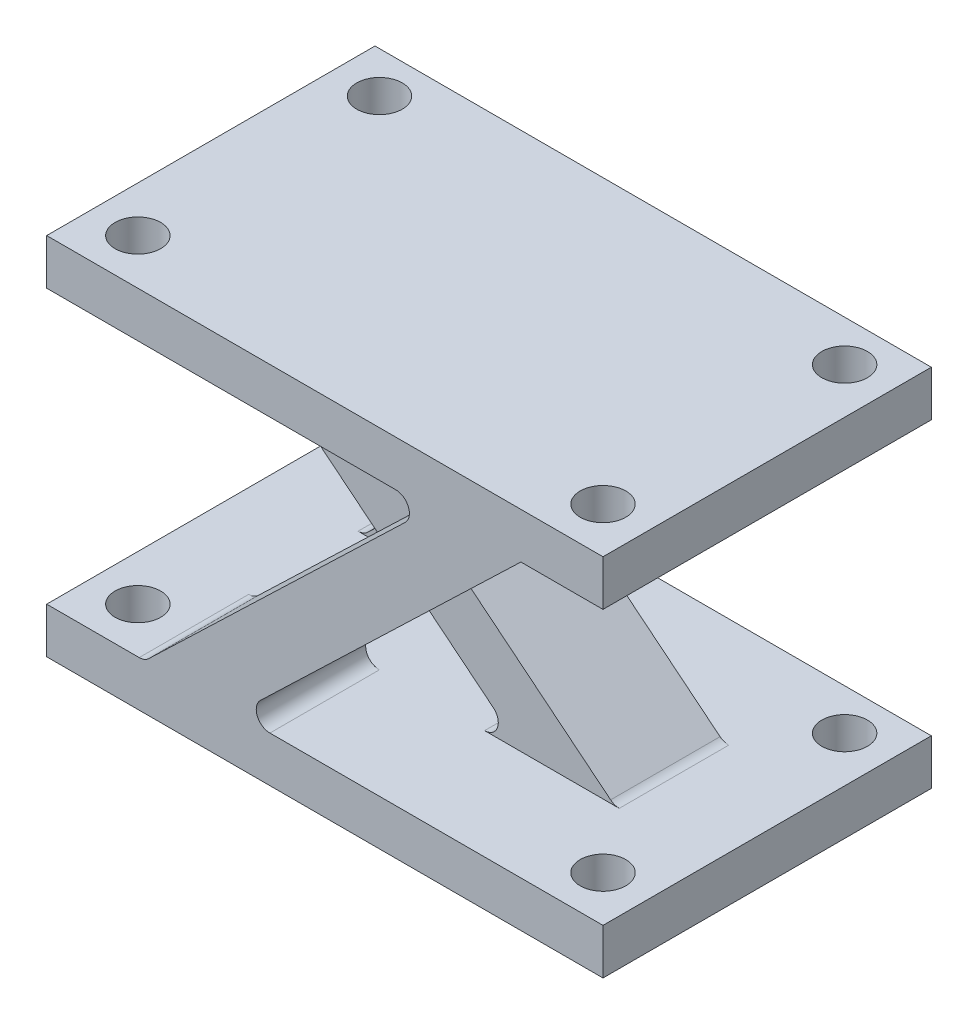
SolidWorks part; units mm, degrees
ref_plane "Front Plane" through (0, 0, 0) normal (0, 0, 1) x (1, 0, 0)
ref_plane "Top Plane" through (0, 0, 0) normal (0, 1, 0) x (1, 0, 0)
ref_plane "Right Plane" through (0, 0, 0) normal (1, 0, 0) x (0, 0, -1)
sketch "Sketch1" plane through (0, 0, 0) normal (0, 1, 0) x (1, 0, 0)
  line L1 (-30.5, -18) -> (30.5, -18)
  line L2 (-30.5, -18) -> (-30.5, 18)
  line L3 (-30.5, 18) -> (30.5, 18)
  line L4 (30.5, -18) -> (30.5, 18)
  line L5 (-30.5, -18) -> (30.5, 18) construction
  line L6 (-30.5, 18) -> (30.5, -18) construction
  circle A0 centre (-25.5, 13.494) radius 2.5
  circle A1 centre (25.5, 13.494) radius 2.5
  circle A2 centre (25.5, -13) radius 2.5
  circle A3 centre (-25.5, -13) radius 2.5
  point P0 (0, 0)
  point P8 (-26.5, -15.2276)
  point P9 (0, 0)
  point P10 (-25.5, -15)
  point P17 (-46.5891, -11.4362)
  dimension "D3" = 5
  dimension "D1" = 36
  dimension "D2" = 61
  dimension "D4" = 5
  dimension "D5" = 4.506
  dimension "D8" = 5
  dimension "D9" = 5
  dimension "D6" = 2
  dimension "D7" = 2
extrude "Boss-Extrude1" add sketch "Sketch1" along normal blind 5
sketch "Sketch4" plane through (0, 0, 18) normal (0, 0, 1) x (1, 0, 0)
  line L0 (19.75, 5) -> (-17.25, 35)
  line L1 (-30.5, 5) -> (30.5, 5) construction
  line L2 (-17.25, 35) -> (-27.25, 35)
  line L3 (-27.25, 35) -> (9.75, 5)
  line L4 (9.75, 5) -> (19.75, 5)
  line L5 (30.5, 5) -> (30.5, 0) construction
  point P8 (0, 0)
  dimension "D1" = 30
  dimension "D2" = 10.75
  dimension "D3" = 20.75
  dimension "D4" = 57.75
extrude "Boss-Extrude3" add sketch "Sketch4" against normal mid plane 12 from surface at -18 starting at plane "Front Plane"
sketch "Sketch3" plane through (0, 0, 18) normal (0, 0, 1) x (1, 0, 0)
  line L0 (-19.75, 5) -> (11.5, 35)
  line L1 (-30.5, 5) -> (30.5, 5) construction
  line L2 (11.5, 35) -> (21.5, 35)
  line L3 (21.5, 35) -> (-9.75, 5)
  line L4 (-9.75, 5) -> (-19.75, 5)
  line L5 (-30.5, 5) -> (-30.5, 0) construction
  dimension "D1" = 30
  dimension "D2" = 10.75
  dimension "D3" = 20.75
  dimension "D4" = 52
extrude "Boss-Extrude2" add sketch "Sketch3" against normal blind 12
mirror "Mirror1" about plane through (0, 0, 0) normal (0, 0, 1) of "Boss-Extrude2"
fillet "Fillet1" radius 1.5 1 edges at (-9.75, 5, 12)
fillet "Fillet2" radius 1.5 1 edges at (-9.75, 5, -12)
fillet "Fillet3" radius 1.5 1 edges at (9.75, 5, 0)
fillet "Fillet4" radius 1.5 3 edges at (19.75, 5, 0) (-19.75, 5, -12) (-19.75, 5, 12)
sketch "Sketch5" plane through (0, 35, 0) normal (0, 1, 0) x (1, 0, 0)
  line L1 (-30.5, -18) -> (30.5, -18)
  line L2 (-30.5, -18) -> (-30.5, 18)
  line L3 (-30.5, 18) -> (30.5, 18)
  line L4 (30.5, -18) -> (30.5, 18)
  circle A0 centre (-25.5, -13) radius 2.5
  circle A1 centre (-25.5, 13.494) radius 2.5
  circle A2 centre (25.5, 13.494) radius 2.5
  circle A3 centre (25.5, -13) radius 2.5
extrude "Boss-Extrude4" add sketch "Sketch5" along normal blind 5
fillet "Fillet5" radius 1.5 1 edges at (11.5, 35, 12)
fillet "Fillet6" radius 1.5 1 edges at (11.5, 35, -12)
fillet "Fillet7" radius 1.5 1 edges at (-17.25, 35, 0)
